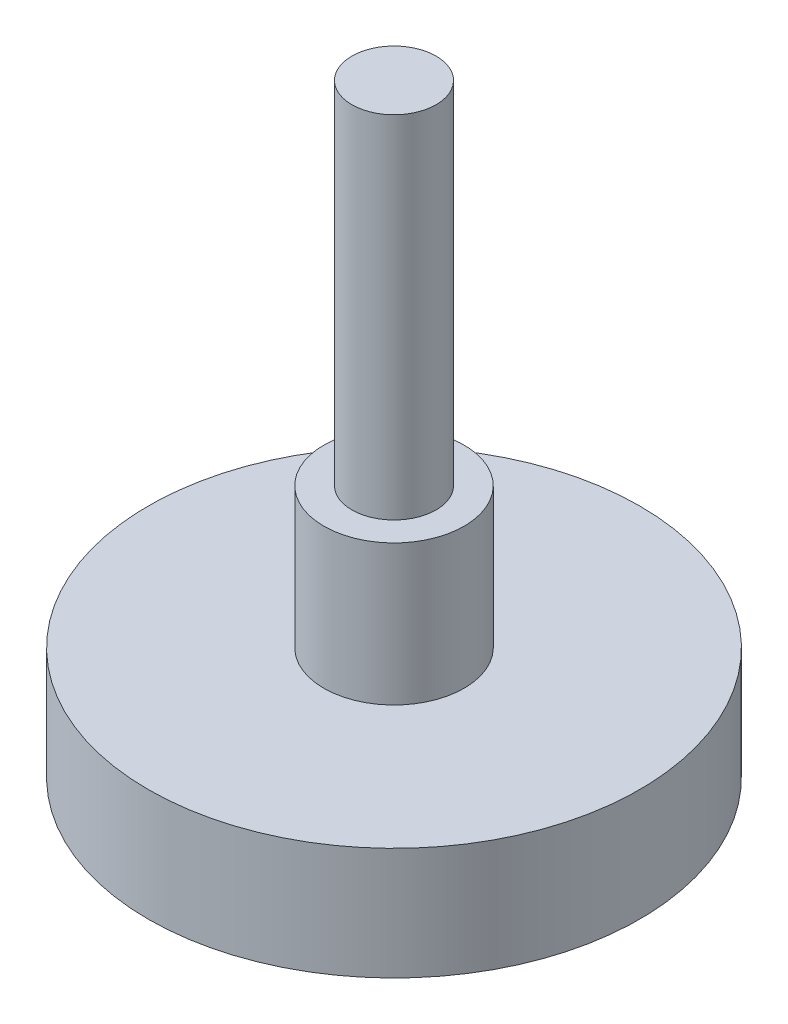
SolidWorks part; units mm, degrees
ref_plane "Front Plane" through (0, 0, 0) normal (0, 0, 1) x (1, 0, 0)
ref_plane "Top Plane" through (0, 0, 0) normal (0, 1, 0) x (1, 0, 0)
ref_plane "Right Plane" through (0, 0, 0) normal (1, 0, 0) x (0, 0, -1)
sketch "Sketch2" plane through (0, 0, 0) normal (0, 1, 0) x (1, 0, 0)
  circle A0 centre (0, 0) radius 17.5
  dimension "D1" = 35
extrude "Boss-Extrude1" add sketch "Sketch2" along normal blind 8
sketch "Sketch3" plane through (0, 8, 0) normal (0, 1, 0) x (1, 0, 0)
  circle A0 centre (0, 0) radius 5
  dimension "D1" = 10
extrude "Boss-Extrude2" add sketch "Sketch3" along normal blind 10
sketch "Sketch4" plane through (0, 18, 0) normal (0, 1, 0) x (1, 0, 0)
  circle A0 centre (0, 0) radius 3
  dimension "D1" = 6
extrude "Boss-Extrude3" add sketch "Sketch4" along normal blind 25
